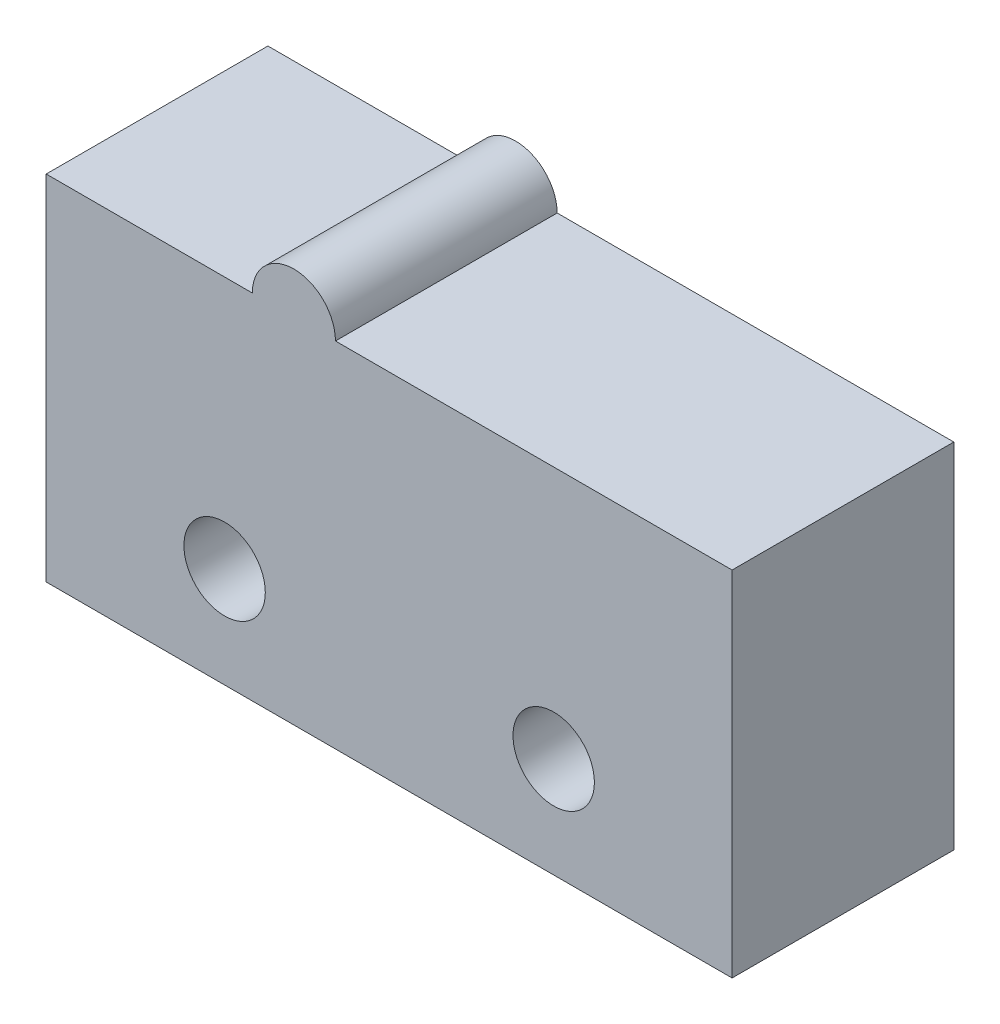
SolidWorks part; units mm, degrees
ref_plane "Front Plane" through (0, 0, 0) normal (0, 0, 1) x (1, 0, 0)
ref_plane "Top Plane" through (0, 0, 0) normal (0, 1, 0) x (1, 0, 0)
ref_plane "Right Plane" through (0, 0, 0) normal (1, 0, 0) x (0, 0, -1)
sketch "Sketch1" plane through (0, 0, 0) normal (0, 0, 1) x (1, 0, 0)
  line L0 (0, 0) -> (19.8, 0)
  line L1 (19.8, 0) -> (19.8, 10.2)
  line L2 (19.8, 10.2) -> (8.35, 10.2)
  line L3 (5.95, 10.2) -> (0, 10.2)
  line L4 (0, 10.2) -> (0, 0)
  line L5 (5.15, 2.9) -> (14.65, 2.9) construction
  line L6 (9.9, 0) -> (9.9, 10.2) construction
  arc A0 (8.35, 10.2) -> (5.95, 10.2) centre (7.15, 10.2) ccw
  circle A1 centre (14.65, 2.9) radius 1.175
  circle A2 centre (5.15, 2.9) radius 1.175
  point P14 (9.9, 2.9)
  point P15 (7.15, 11.4)
  dimension "D1" = 19.8
  dimension "D3" = 2.9
  dimension "D5" = 2.35
  dimension "D2" = 10.2
  dimension "D4" = 9.5
  dimension "D6" = 8.5
  dimension "D7" = 7.5
extrude "Boss-Extrude1" add sketch "Sketch1" along normal blind 6.4
